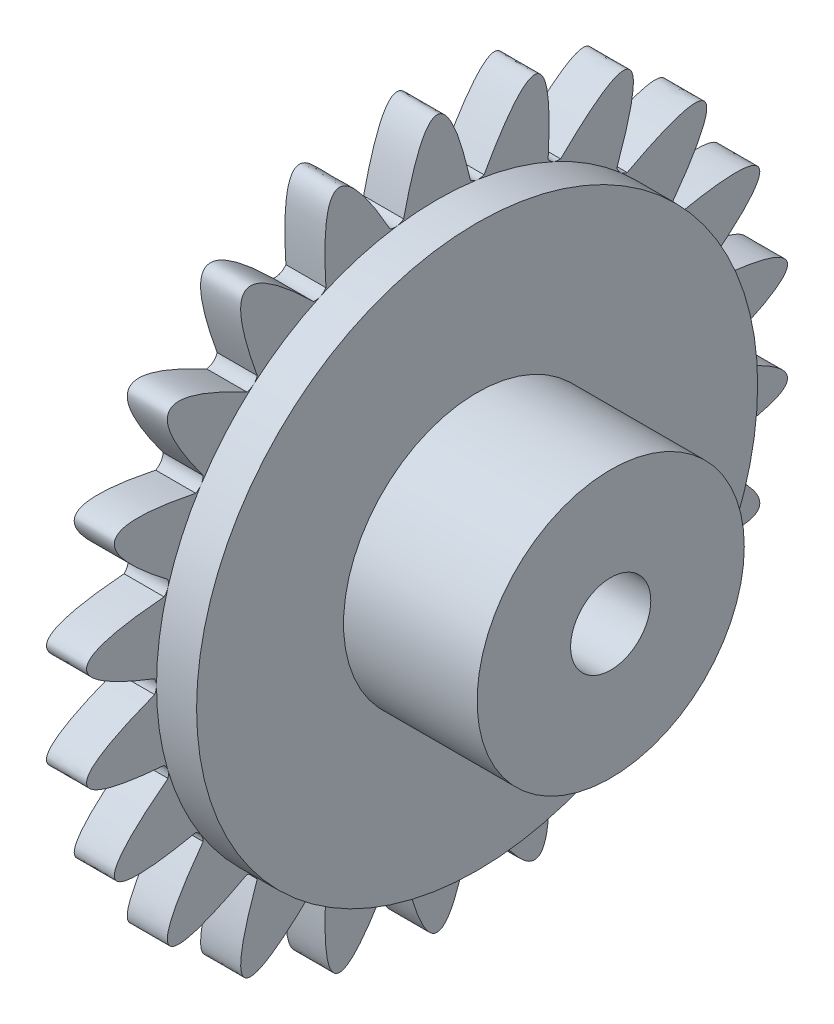
SolidWorks part; units mm, degrees
ref_plane "Front Plane" through (0, 0, 0) normal (0, 0, 1) x (1, 0, 0)
ref_plane "Top Plane" through (0, 0, 0) normal (0, 1, 0) x (1, 0, 0)
ref_plane "Right Plane" through (0, 0, 0) normal (1, 0, 0) x (0, 0, -1)
sketch "Sketch1" plane through (0, 0, 0) normal (1, 0, 0) x (0, 0, -1)
  circle A0 centre (0, 0) radius 21
  dimension "D1" = 42
extrude "Boss-Extrude1" add sketch "Sketch1" along normal blind 3
sketch "Sketch2" plane through (3, 0, 0) normal (1, 0, 0) x (0, 0, -1)
  circle A0 centre (0, 0) radius 10
  dimension "D1" = 20
extrude "Boss-Extrude2" add sketch "Sketch2" along normal blind 10
sketch "Sketch3" plane through (13, 0, 0) normal (1, 0, 0) x (0, 0, -1)
  circle A0 centre (0, 0) radius 3
extrude "Cut-Extrude1" cut sketch "Sketch3" against normal blind 10
sketch "Sketch4" plane through (0, 0, 0) normal (-1, 0, 0) x (0, 0, 1)
  line L0 (0, 21) -> (0, 26.5) construction
  line L1 (0, 21) -> (2.5, 21) construction
  line L2 (0, 21) -> (-2.5, 21) construction
  circle A1 centre (0, 0) radius 21 construction
  spline S0 degree 2 poles (-2.5, 21) (0, 32) (2.5, 21) knots 0 0 0 1 1 1
  spline S1 degree 2 poles (3.5177, 20.8537) (9.0154, 30.7038) (8.3151, 19.445) knots 0 0 0 1 1 1
  spline S2 degree 2 poles (9.2503, 19.0179) (17.3005, 26.9201) (13.4566, 16.3147) knots 0 0 0 1 1 1
  spline S3 degree 2 poles (14.2336, 15.6414) (24.184, 20.9555) (17.5079, 11.8627) knots 0 0 0 1 1 1
  spline S4 degree 2 poles (18.0637, 10.9978) (29.1082, 13.2933) (20.1408, 6.4496) knots 0 0 0 1 1 1
  spline S5 degree 2 poles (20.4305, 5.4632) (31.6743, 4.5541) (21.142, 0.5141) knots 0 0 0 1 1 1
  spline S6 degree 2 poles (21.142, -0.5141) (31.6743, -4.5541) (20.4305, -5.4632) knots 0 0 0 1 1 1
  spline S7 degree 2 poles (20.1408, -6.4496) (29.1082, -13.2933) (18.0637, -10.9978) knots 0 0 0 1 1 1
  spline S8 degree 2 poles (17.5079, -11.8627) (24.184, -20.9555) (14.2336, -15.6414) knots 0 0 0 1 1 1
  spline S9 degree 2 poles (13.4566, -16.3147) (17.3005, -26.9201) (9.2503, -19.0179) knots 0 0 0 1 1 1
  spline S10 degree 2 poles (8.3151, -19.445) (9.0154, -30.7038) (3.5177, -20.8537) knots 0 0 0 1 1 1
  spline S11 degree 2 poles (2.5, -21) (0, -32) (-2.5, -21) knots 0 0 0 1 1 1
  spline S12 degree 2 poles (-3.5177, -20.8537) (-9.0154, -30.7038) (-8.3151, -19.445) knots 0 0 0 1 1 1
  spline S13 degree 2 poles (-9.2503, -19.0179) (-17.3005, -26.9201) (-13.4566, -16.3147) knots 0 0 0 1 1 1
  spline S14 degree 2 poles (-14.2336, -15.6414) (-24.184, -20.9555) (-17.5079, -11.8627) knots 0 0 0 1 1 1
  spline S15 degree 2 poles (-18.0637, -10.9978) (-29.1082, -13.2933) (-20.1408, -6.4496) knots 0 0 0 1 1 1
  spline S16 degree 2 poles (-20.4305, -5.4632) (-31.6743, -4.5541) (-21.142, -0.5141) knots 0 0 0 1 1 1
  spline S17 degree 2 poles (-21.142, 0.5141) (-31.6743, 4.5541) (-20.4305, 5.4632) knots 0 0 0 1 1 1
  spline S18 degree 2 poles (-20.1408, 6.4496) (-29.1082, 13.2933) (-18.0637, 10.9978) knots 0 0 0 1 1 1
  spline S19 degree 2 poles (-17.5079, 11.8627) (-24.184, 20.9555) (-14.2336, 15.6414) knots 0 0 0 1 1 1
  spline S20 degree 2 poles (-13.4566, 16.3147) (-17.3005, 26.9201) (-9.2503, 19.0179) knots 0 0 0 1 1 1
  spline S21 degree 2 poles (-8.3151, 19.445) (-9.0154, 30.7038) (-3.5177, 20.8537) knots 0 0 0 1 1 1
  spline S22 degree 2 poles (-3.5177, 20.8537) (-2.9673, 20.6458) (-2.5, 21) knots 0 0 0 1 1 1
  spline S23 degree 2 poles (2.5, 21) (2.9695, 20.6454) (3.5177, 20.8537) knots 0 0 0 1 1 1
  spline S24 degree 2 poles (8.3151, 19.445) (8.6657, 18.9726) (9.2503, 19.0179) knots 0 0 0 1 1 1
  spline S25 degree 2 poles (13.4566, 16.3147) (13.6598, 15.7626) (14.2336, 15.6414) knots 0 0 0 1 1 1
  spline S26 degree 2 poles (17.5079, 11.8627) (17.5474, 11.2757) (18.0637, 10.9978) knots 0 0 0 1 1 1
  spline S27 degree 2 poles (20.1408, 6.4496) (20.0133, 5.8753) (20.4305, 5.4632) knots 0 0 0 1 1 1
  spline S28 degree 2 poles (21.142, 0.5141) (20.8579, -0.0011) (21.142, -0.5141) knots 0 0 0 1 1 1
  spline S29 degree 2 poles (20.4305, -5.4632) (20.0127, -5.8774) (20.1408, -6.4496) knots 0 0 0 1 1 1
  spline S30 degree 2 poles (18.0637, -10.9978) (17.5462, -11.2776) (17.5079, -11.8627) knots 0 0 0 1 1 1
  spline S31 degree 2 poles (14.2336, -15.6414) (13.6582, -15.7641) (13.4566, -16.3147) knots 0 0 0 1 1 1
  spline S32 degree 2 poles (9.2503, -19.0179) (8.6637, -18.9735) (8.3151, -19.445) knots 0 0 0 1 1 1
  spline S33 degree 2 poles (3.5177, -20.8537) (2.9673, -20.6458) (2.5, -21) knots 0 0 0 1 1 1
  spline S34 degree 2 poles (-2.5, -21) (-2.9695, -20.6454) (-3.5177, -20.8537) knots 0 0 0 1 1 1
  spline S35 degree 2 poles (-8.3151, -19.445) (-8.6657, -18.9726) (-9.2503, -19.0179) knots 0 0 0 1 1 1
  spline S36 degree 2 poles (-13.4566, -16.3147) (-13.6598, -15.7626) (-14.2336, -15.6414) knots 0 0 0 1 1 1
  spline S37 degree 2 poles (-17.5079, -11.8627) (-17.5474, -11.2757) (-18.0637, -10.9978) knots 0 0 0 1 1 1
  spline S38 degree 2 poles (-20.1408, -6.4496) (-20.0133, -5.8753) (-20.4305, -5.4632) knots 0 0 0 1 1 1
  spline S39 degree 2 poles (-21.142, -0.5141) (-20.8579, 0.0011) (-21.142, 0.5141) knots 0 0 0 1 1 1
  spline S40 degree 2 poles (-20.4305, 5.4632) (-20.0127, 5.8774) (-20.1408, 6.4496) knots 0 0 0 1 1 1
  spline S41 degree 2 poles (-18.0637, 10.9978) (-17.5462, 11.2776) (-17.5079, 11.8627) knots 0 0 0 1 1 1
  spline S42 degree 2 poles (-14.2336, 15.6414) (-13.6582, 15.7641) (-13.4566, 16.3147) knots 0 0 0 1 1 1
  spline S43 degree 2 poles (-9.2503, 19.0179) (-8.6637, 18.9735) (-8.3151, 19.445) knots 0 0 0 1 1 1
  point P75 (0, 0)
  point P140 (0, 0)
  circle M48 centre (0, 0) radius 21
  dimension "D2" = 2.5
  dimension "D3" = 2.5
extrude "Boss-Extrude3" add sketch "Sketch4" along normal blind 3 contours S43 S42 S41 S40 S39 S38 S37 S36 S35 S34 S33 S32 S31 S30 S29 S28 S27 S26 S25 S24 S23 S22 M48 | S42 S19 S41 M48 | S43 S20 S42 M48 | S43 S22 S21 M48 | S23 S0 S22 M48 | S24 S1 S23 M48 | S25 S2 S24 M48 | S26 S3 S25 M48 | S27 S4 S26 M48 | S28 S5 S27 M48 | S29 S6 S28 M48 | S30 S7 S29 M48 | S31 S8 S30 M48 | S32 S9 S31 M48 | S33 S10 S32 M48 | S34 S11 S33 M48 | S35 S12 S34 M48 | S36 S13 S35 M48 | S37 S14 S36 M48 | S38 S15 S37 M48 | S39 S16 S38 M48 | S40 S17 S39 M48 | S41 S18 S40 M48
